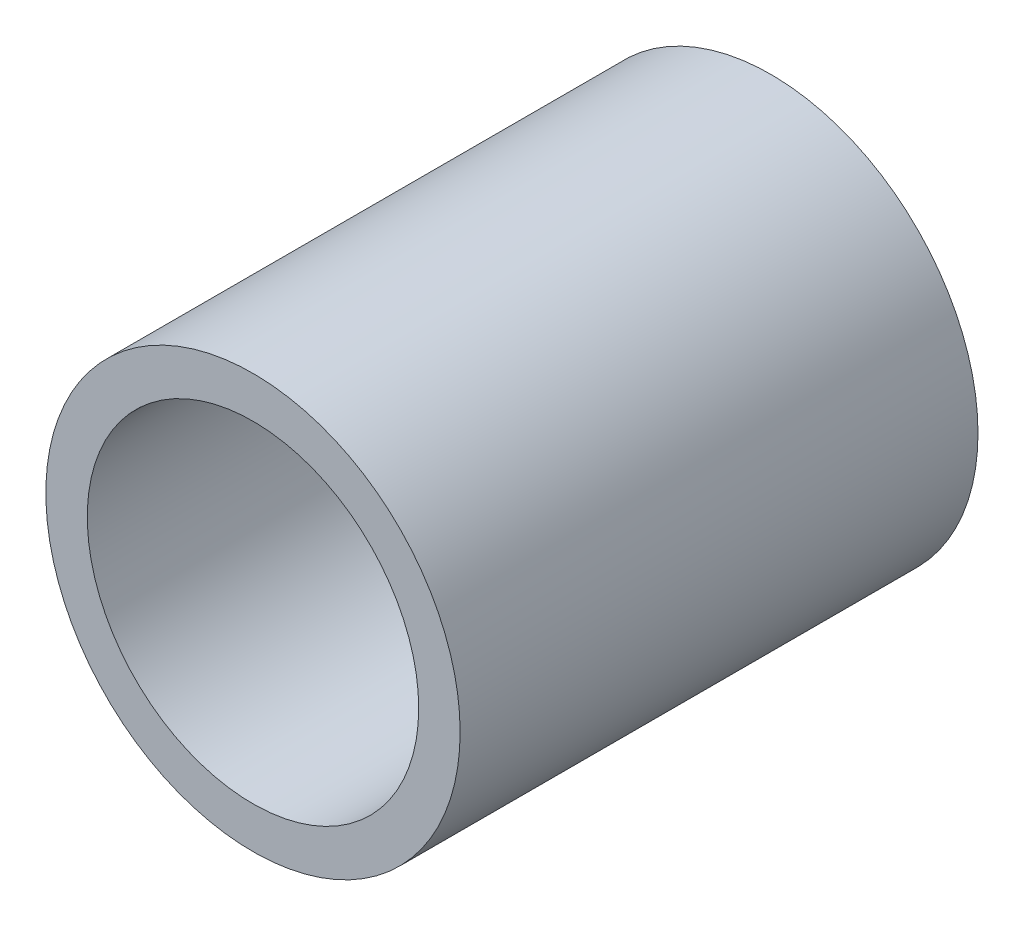
SolidWorks part; units mm, degrees
material "Nylon 101"
ref_plane "Front Plane" through (0, 0, 0) normal (0, 0, 1) x (1, 0, 0)
ref_plane "Top Plane" through (0, 0, 0) normal (0, 1, 0) x (1, 0, 0)
ref_plane "Right Plane" through (0, 0, 0) normal (1, 0, 0) x (0, 0, -1)
sketch "Sketch1" plane through (0, 0, 0) normal (0, 0, 1) x (1, 0, 0)
  circle A0 centre (0, 0) radius 1.6
  circle A1 centre (0, 0) radius 2
  dimension "D1" = 4
  dimension "D2" = 3.2
extrude "Boss-Extrude1" add sketch "Sketch1" along normal blind 5
